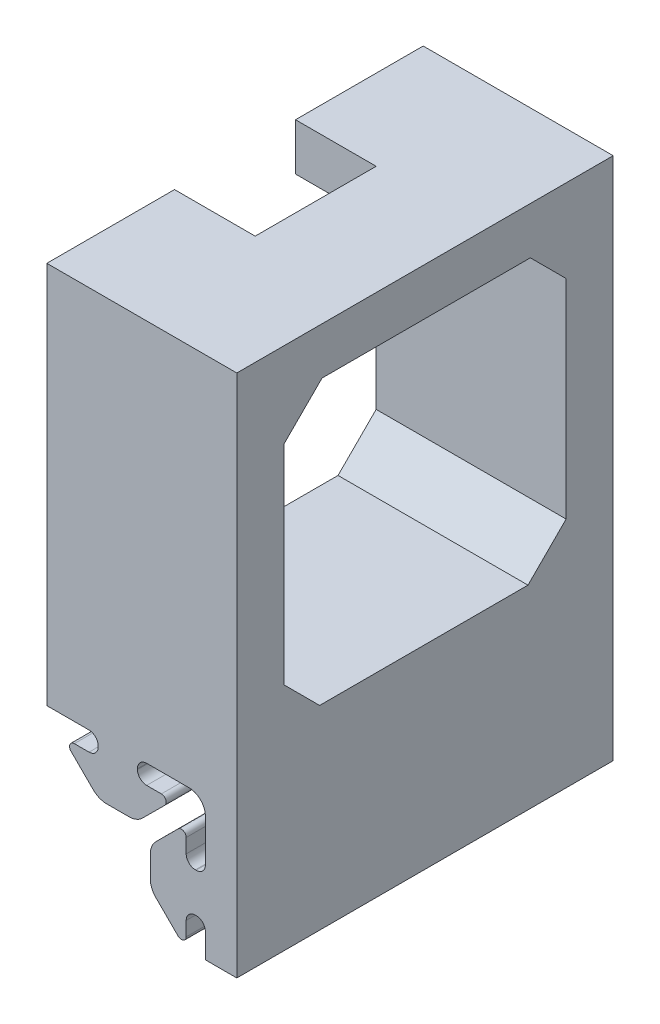
SolidWorks part; units mm, degrees
ref_plane "Front Plane" through (0, 0, 0) normal (0, 0, 1) x (1, 0, 0)
ref_plane "Top Plane" through (0, 0, 0) normal (0, 1, 0) x (1, 0, 0)
ref_plane "Right Plane" through (0, 0, 0) normal (1, 0, 0) x (0, 0, -1)
sketch "Sketch1" plane through (0, 0, 0) normal (0, 0, 1) x (1, 0, 0)
  line L0 (13.02, -7.9417) -> (17.7, -7.9417)
  line L1 (-10.5664, 13.02) -> (-10.5664, 70.02)
  line L2 (-10.5664, 70.02) -> (17.7, 70.02)
  line L3 (17.7, -7.9417) -> (17.7, 70.02)
  line L10 (12.7, -6.3331) -> (12.7, -7.9417) construction
  line L11 (13.02, -5.3171) -> (13.02, -4.2875)
  line L12 (11.651, -2.9185) -> (11.5392, -2.9185)
  line L13 (10.1702, -4.2875) -> (10.1702, -6.4021)
  line L14 (8.9631, -6.9029) -> (5.667, -3.6143)
  line L15 (4.8285, -1.5932) -> (4.8285, 1.5932)
  line L16 (5.667, 3.6143) -> (8.9631, 6.9029)
  line L17 (10.1702, 6.4021) -> (10.1702, 4.2875)
  line L18 (11.5392, 2.9185) -> (11.651, 2.9185)
  line L19 (13.02, 10.5773) -> (13.02, 4.2875)
  line L20 (6.3329, 13.02) -> (10.5626, 13.0198)
  line L22 (6.3329, 13.02) -> (4.2875, 13.02)
  line L23 (2.9185, 11.651) -> (2.9185, 11.5392)
  line L24 (4.2875, 10.1702) -> (6.4768, 10.1702)
  line L25 (6.981, 8.9509) -> (3.6723, 5.6497)
  line L26 (1.6558, 4.8158) -> (-1.6558, 4.8158)
  line L27 (-3.6723, 5.6497) -> (-6.981, 8.9509)
  line L28 (-6.4768, 10.1702) -> (-4.2875, 10.1702)
  line L29 (-2.9185, 11.5392) -> (-2.9185, 11.651)
  line L30 (-4.2875, 13.02) -> (-5.3171, 13.02)
  line L31 (-5.3171, 13.02) -> (-10.5664, 13.02)
  line L32 (13.02, -5.3171) -> (13.02, -7.9417)
  line L33 (13.02, -6.3331) -> (13.02, -7.9417) construction
  line L34 (13.02, 4.2875) -> (13.02, 5.3171) construction
  line L37 (5.3171, 13.02) -> (4.2875, 13.02) construction
  line L38 (-6.3331, 13.02) -> (-9.5504, 13.02) construction
  line L96 (12.7, -5.3171) -> (12.7, -4.2875) construction
  line L97 (11.651, -3.2385) -> (11.5392, -3.2385) construction
  line L98 (10.4902, -4.2875) -> (10.4902, -6.4021) construction
  line L99 (8.7371, -7.1294) -> (5.441, -3.8408) construction
  line L100 (4.5085, -1.5932) -> (4.5085, 1.5932) construction
  line L101 (5.441, 3.8408) -> (8.7371, 7.1294) construction
  line L102 (10.4902, 6.4021) -> (10.4902, 4.2875) construction
  line L103 (11.5392, 3.2385) -> (11.651, 3.2385) construction
  line L104 (12.7, 4.2875) -> (12.7, 5.3171) construction
  line L105 (12.7, 6.3331) -> (12.7, 9.5504) construction
  line L106 (9.5504, 12.7) -> (6.3331, 12.7) construction
  line L107 (5.3171, 12.7) -> (4.2875, 12.7) construction
  line L108 (3.2385, 11.651) -> (3.2385, 11.5392) construction
  line L109 (4.2875, 10.4902) -> (6.4768, 10.4902) construction
  line L110 (7.207, 8.7244) -> (3.8983, 5.4232) construction
  line L111 (1.6558, 4.4958) -> (-1.6558, 4.4958) construction
  line L112 (-3.8983, 5.4232) -> (-7.207, 8.7244) construction
  line L113 (-6.4768, 10.4902) -> (-4.2875, 10.4902) construction
  line L114 (-3.2385, 11.5392) -> (-3.2385, 11.651) construction
  line L115 (-4.2875, 12.7) -> (-5.3171, 12.7) construction
  line L116 (-6.3331, 12.7) -> (-9.5504, 12.7) construction
  arc A0 (13.02, -4.2875) -> (11.651, -2.9185) centre (11.651, -4.2875) ccw
  arc A1 (11.5392, -2.9185) -> (10.1702, -4.2875) centre (11.5392, -4.2875) ccw
  arc A2 (8.9631, -6.9029) -> (10.1702, -6.4021) centre (9.4628, -6.4021) ccw
  arc A3 (4.8285, -1.5932) -> (5.667, -3.6143) centre (7.6835, -1.5932) ccw
  arc A4 (5.667, 3.6143) -> (4.8285, 1.5932) centre (7.6835, 1.5932) ccw
  arc A5 (10.1702, 6.4021) -> (8.9631, 6.9029) centre (9.4628, 6.4021) ccw
  arc A6 (10.1702, 4.2875) -> (11.5392, 2.9185) centre (11.5392, 4.2875) ccw
  arc A7 (11.651, 2.9185) -> (13.02, 4.2875) centre (11.651, 4.2875) ccw
  arc A8 (4.2875, 13.02) -> (2.9185, 11.651) centre (4.2875, 11.651) ccw
  arc A9 (2.9185, 11.5392) -> (4.2875, 10.1702) centre (4.2875, 11.5392) ccw
  arc A10 (6.981, 8.9509) -> (6.4768, 10.1702) centre (6.4768, 9.4563) ccw
  arc A11 (1.6558, 4.8158) -> (3.6723, 5.6497) centre (1.6558, 7.6708) ccw
  arc A12 (-3.6723, 5.6497) -> (-1.6558, 4.8158) centre (-1.6558, 7.6708) ccw
  arc A13 (-6.4768, 10.1702) -> (-6.981, 8.9509) centre (-6.4768, 9.4563) ccw
  arc A14 (-4.2875, 10.1702) -> (-2.9185, 11.5392) centre (-4.2875, 11.5392) ccw
  arc A15 (-2.9185, 11.651) -> (-4.2875, 13.02) centre (-4.2875, 11.651) ccw
  arc A16 (13.02, 10.5773) -> (10.5626, 13.0198) centre (10.5918, 10.5918) ccw
  arc A17 (13.0198, 10.5625) -> (10.5626, 13.0198) centre (10.5918, 10.5918) ccw construction
  arc A114 (12.7, -5.3171) -> (12.7, -6.3331) centre (12.7, -5.8251) ccw construction
  arc A115 (12.7, -4.2875) -> (11.651, -3.2385) centre (11.651, -4.2875) ccw construction
  arc A116 (11.5392, -3.2385) -> (10.4902, -4.2875) centre (11.5392, -4.2875) ccw construction
  arc A117 (8.7371, -7.1294) -> (10.4902, -6.4021) centre (9.4628, -6.4021) ccw construction
  arc A118 (4.5085, -1.5932) -> (5.441, -3.8408) centre (7.6835, -1.5932) ccw construction
  arc A119 (5.441, 3.8408) -> (4.5085, 1.5932) centre (7.6835, 1.5932) ccw construction
  arc A120 (10.4902, 6.4021) -> (8.7371, 7.1294) centre (9.4628, 6.4021) ccw construction
  arc A121 (10.4902, 4.2875) -> (11.5392, 3.2385) centre (11.5392, 4.2875) ccw construction
  arc A122 (11.651, 3.2385) -> (12.7, 4.2875) centre (11.651, 4.2875) ccw construction
  arc A123 (12.7, 6.3331) -> (12.7, 5.3171) centre (12.7, 5.8251) ccw construction
  arc A124 (12.6998, 10.5664) -> (12.7, 9.5504) centre (12.7, 10.0584) ccw construction
  arc A125 (12.6998, 10.5664) -> (10.5664, 12.6998) centre (10.5918, 10.5918) ccw construction
  arc A126 (9.5504, 12.7) -> (10.5664, 12.6998) centre (10.0584, 12.7) ccw construction
  arc A127 (5.3171, 12.7) -> (6.3331, 12.7) centre (5.8251, 12.7) ccw construction
  arc A128 (4.2875, 12.7) -> (3.2385, 11.651) centre (4.2875, 11.651) ccw construction
  arc A129 (3.2385, 11.5392) -> (4.2875, 10.4902) centre (4.2875, 11.5392) ccw construction
  arc A130 (7.207, 8.7244) -> (6.4768, 10.4902) centre (6.4768, 9.4563) ccw construction
  arc A131 (1.6558, 4.4958) -> (3.8983, 5.4232) centre (1.6558, 7.6708) ccw construction
  arc A132 (-3.8983, 5.4232) -> (-1.6558, 4.4958) centre (-1.6558, 7.6708) ccw construction
  arc A133 (-6.4768, 10.4902) -> (-7.207, 8.7244) centre (-6.4768, 9.4563) ccw construction
  arc A134 (-4.2875, 10.4902) -> (-3.2385, 11.5392) centre (-4.2875, 11.5392) ccw construction
  arc A135 (-3.2385, 11.651) -> (-4.2875, 12.7) centre (-4.2875, 11.651) ccw construction
  arc A136 (-6.3331, 12.7) -> (-5.3171, 12.7) centre (-5.8251, 12.7) ccw construction
  arc A137 (-10.5664, 12.6998) -> (-9.5504, 12.7) centre (-10.0584, 12.7) ccw construction
  dimension "D1" = 57
  dimension "D6" = 5
  dimension "D8" = 0.32
  dimension "D7" = 6.2898
  dimension "D9" = 4.2297
extrude "Boss-Extrude1" add sketch "Sketch1" along normal blind 56 contours L3 L2 L1 L31 L30 A15 L29 A14 L28 A13 L27 A12 L26 A11 L25 A10 L24 A9 L23 A8 L22 L20 A16 L19 A7 L18 A6 L17 A5 L16 A4 L15 A3 L14 A2 L13 A1 L12 A0 L11 L32 L0
sketch "Sketch14" plane through (17.7, 0, 0) normal (1, 0, 0) x (0, 0, -1)
  line L0 (-43.6752, 21.02) -> (-12.6752, 21.02)
  line L1 (-7, 26.6952) -> (-7, 57.6952)
  line L2 (-12.3248, 63.02) -> (-43.3248, 63.02)
  line L3 (-49, 57.3448) -> (-49, 26.3448)
  line L4 (-56, -7.9417) -> (-56, 70.02) construction
  line L6 (-56, 70.02) -> (0, 70.02) construction
  line L7 (-43.6752, 21.02) -> (-49, 26.3448)
  line L8 (-49, 57.3448) -> (-43.3248, 63.02)
  line L9 (-12.3248, 63.02) -> (-7, 57.6952)
  line L10 (-12.6752, 21.02) -> (-7, 26.6952)
  dimension "D3" = 7
  dimension "D4" = 7
  dimension "D5" = 31
  dimension "D6" = 31
  dimension "D7" = 31
  dimension "D8" = 31
  dimension "D9" = 45
  dimension "D10" = 45
extrude "Cut-Extrude1" cut sketch "Sketch14" against normal blind 56
sketch "Sketch15" plane through (0, 70.02, 0) normal (0, 1, 0) x (1, 0, 0)
  line L1 (-10.5664, -56) -> (-10.5664, 0) construction
  line L2 (-10.5664, -19) -> (1.4336, -19)
  line L3 (1.4336, -19) -> (1.4336, -37)
  line L4 (1.4336, -37) -> (-10.5664, -37)
  line L6 (-10.5664, -19) -> (-15.1003, -19)
  line L7 (-15.1003, -19) -> (-15.1003, -37)
  line L8 (-15.1003, -37) -> (-10.5664, -37)
  dimension "D3" = 12
extrude "Cut-Extrude2" cut sketch "Sketch15" against normal blind 10
